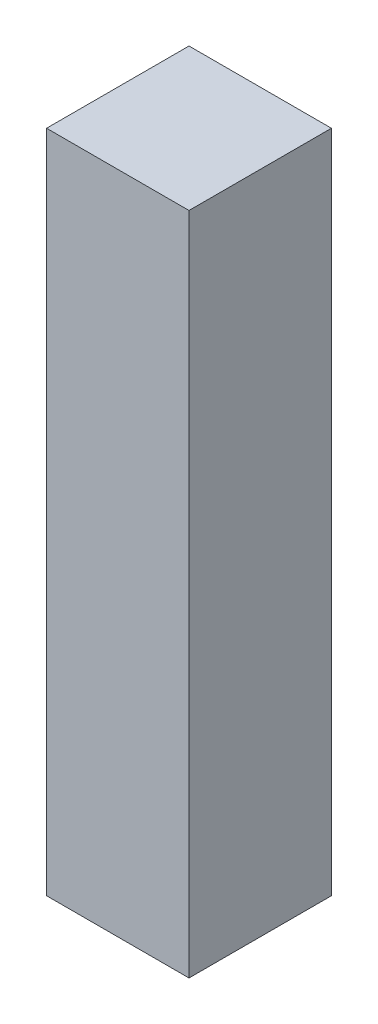
SolidWorks part; units mm, degrees
ref_plane "Front Plane" through (0, 0, 0) normal (0, 0, 1) x (1, 0, 0)
ref_plane "Top Plane" through (0, 0, 0) normal (0, 1, 0) x (1, 0, 0)
ref_plane "Right Plane" through (0, 0, 0) normal (1, 0, 0) x (0, 0, -1)
sketch "Sketch1" plane through (0, 0, 0) normal (0, 1, 0) x (1, 0, 0)
  line L1 (-3, -3) -> (3, -3)
  line L2 (-3, -3) -> (-3, 3)
  line L3 (-3, 3) -> (3, 3)
  line L4 (3, -3) -> (3, 3)
  line L5 (-3, -3) -> (3, 3) construction
  line L6 (-3, 3) -> (3, -3) construction
  point P0 (0, 0)
  dimension "D1" = 6
  dimension "D2" = 6
extrude "Boss-Extrude1" add sketch "Sketch1" along normal blind 28
